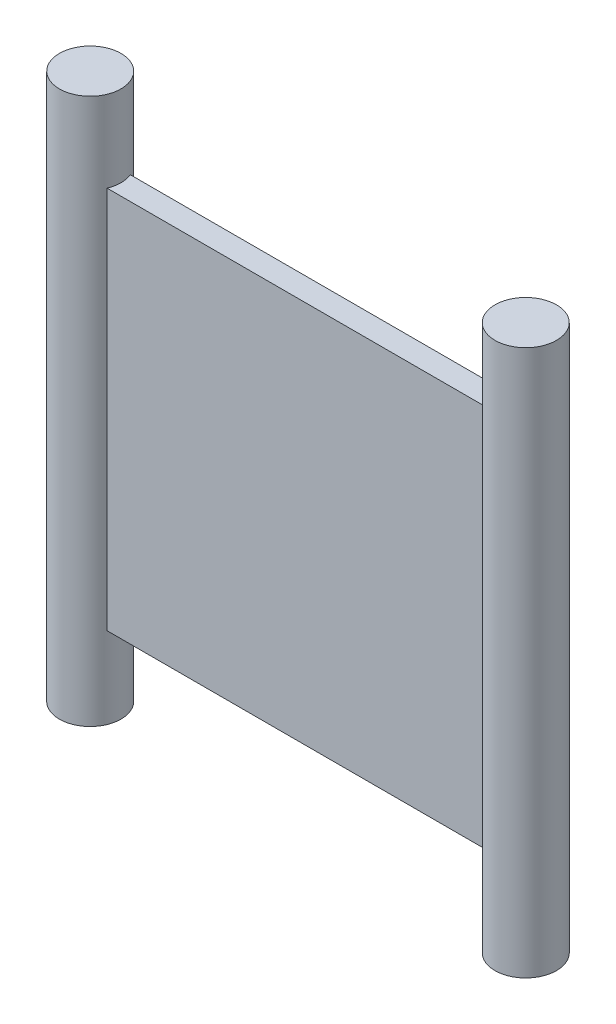
SolidWorks part; units mm, degrees
ref_plane "Front Plane" through (0, 0, 0) normal (0, 0, 1) x (1, 0, 0)
ref_plane "Top Plane" through (0, 0, 0) normal (0, 1, 0) x (1, 0, 0)
ref_plane "Right Plane" through (0, 0, 0) normal (1, 0, 0) x (0, 0, -1)
sketch "Sketch1" plane through (0, 0, 0) normal (0, 1, 0) x (1, 0, 0)
  line L1 (9.375, 0.5) -> (-9.375, 0.5)
  line L2 (9.375, 0.5) -> (9.375, -0.5)
  line L3 (9.375, -0.5) -> (-9.375, -0.5)
  line L4 (-9.375, 0.5) -> (-9.375, -0.5)
  line L5 (9.375, 0.5) -> (-9.375, -0.5) construction
  line L6 (9.375, -0.5) -> (-9.375, 0.5) construction
  point P0 (0, 0)
  dimension "D1" = 18.75
  dimension "D3" = 1
extrude "Boss-Extrude1" add sketch "Sketch1" along normal blind 16.5
ref_plane "Plane1" through (0, 8.25, 0) normal (0, 1, 0) x (1, 0, 0)
sketch "Sketch2" plane through (0, 8.25, 0) normal (0, 1, 0) x (1, 0, 0)
  line L0 (9.375, -0.5) -> (9.375, 0.5) construction
  line L1 (-9.375, 0.5) -> (-9.375, -0.5) construction
  line L2 (9.375, -0.5) -> (9.375, 0.5) construction
  line L3 (-9.375, 0.5) -> (-9.375, -0.5) construction
  circle A0 centre (-9.375, 0) radius 1.325
  circle A1 centre (9.375, 0) radius 1.325
  dimension "D1" = 2.65
extrude "Boss-Extrude2" add sketch "Sketch2" along normal mid plane 23.5
